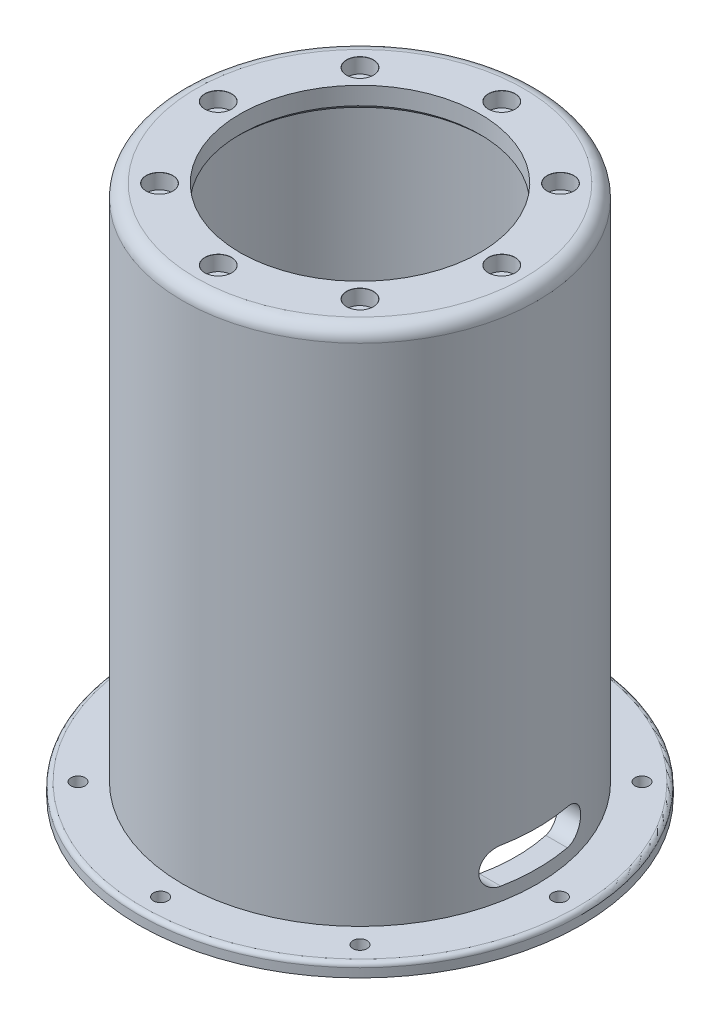
SolidWorks part; units mm, degrees
ref_plane "前视基准面" through (0, 0, 0) normal (0, 0, 1) x (1, 0, 0)
ref_plane "上视基准面" through (0, 0, 0) normal (0, 1, 0) x (1, 0, 0)
ref_plane "右视基准面" through (0, 0, 0) normal (1, 0, 0) x (0, 0, -1)
sketch "草图1" plane through (0, 0, 0) normal (0, 1, 0) x (1, 0, 0)
  circle A0 centre (0, 0) radius 40
  dimension "D1" = 80
extrude "凸台-拉伸1" add sketch "草图1" along normal blind 120
sketch "草图2" plane through (0, 0, 0) normal (0, -1, 0) x (1, 0, 0)
  circle A0 centre (0, 0) radius 35.25
  dimension "D1" = 70.5
extrude "切除-拉伸1" cut sketch "草图2" against normal offset from surface (115 mm away) 5 up to face at (0, 120, 40)
sketch "草图3" plane through (0, 120, 0) normal (0, 1, 0) x (1, 0, 0)
  circle A0 centre (0, 0) radius 27.1
  dimension "D1" = 54.2
extrude "切除-拉伸2" cut sketch "草图3" against normal through all
sketch "草图4" plane through (0, 120, 0) normal (0, 1, 0) x (1, 0, 0)
  circle A0 centre (0, 0) radius 32 construction
  point P3 (0, 32)
  dimension "D1" = 64
hole_wizard "打孔尺寸(%根据)内六角圆柱头螺钉的类型1" positions "草图5" profile "草图6" counterbore size "M3" standard "GB" end condition through all
sketch "草图5" plane through (0, 120, 0) normal (0, 1, 0) x (1, 0, 0)
  point P0 (0, 32)
sketch "草图6" plane through (0, 120, -32) normal (1, 0, 0) x (0, 0, 1)
  line L0 (0, 0) -> (0, 120)
  line L1 (0, 120) -> (1.7, 120)
  line L3 (1.7, 120) -> (1.7, 3.4)
  line L4 (3, 3.4) -> (1.7, 3.4)
  line L5 (3, 3.4) -> (3, 0.025)
  line L6 (3, 0.025) -> (3.025, 0)
  line L7 (3.025, 0) -> (0, 0)
  line L8 (-3, 0.025) -> (-3.025, 0) construction
  line L11 (0, -6.35) -> (0, 107.95) construction
  dimension "通孔孔直径" = 3.4
  dimension "通孔孔深度" = 120
  dimension "柱形沉头孔直径" = 6
  dimension "柱形沉头孔深度" = 3.4
  dimension "近端锥形沉头孔直径" = 6.05
  dimension "近端锥形沉头孔角度" = 90
pattern_circular "阵列(圆周)1" count 8 over 360 about axis through (0, 0, 0) along (0, 1, 0) of "打孔尺寸(%根据)内六角圆柱头螺钉的类型1"
sketch "草图7" plane through (0, 0, 0) normal (0, -1, 0) x (1, 0, 0)
  circle A0 centre (0, 0) radius 50
  circle A1 centre (0, 0) radius 40 construction
  circle A2 centre (0, 0) radius 40
  dimension "D1" = 100
extrude "凸台-拉伸2" add sketch "草图7" against normal blind 3
sketch "草图8" plane through (0, 3, 0) normal (0, 1, 0) x (1, 0, 0)
  circle A2 centre (0, -45) radius 1.6
  circle A3 centre (0, 0) radius 45 construction
  point P7 (0, -45)
  dimension "D1" = 3.2
  dimension "D2" = 90
extrude "切除-拉伸3" cut sketch "草图8" against normal through all
pattern_circular "阵列(圆周)2" count 8 over 360 about axis through (0, 0, 0) along (0, 1, 0) of "切除-拉伸3"
fillet "圆角1" radius 3 1 edges at (0, 120, 40)
chamfer "倒角1" distance 1 angle 45 2 edges at (0, 115, 27.1) (0, 0, -35.25)
fillet "圆角2" radius 1 1 edges at (0, 3, -50)
ref_plane "基准面1" through (40, 0, 0) normal (1, 0, 0) x (0, 0, -1)
sketch "草图9" plane through (40, 0, 0) normal (1, 0, 0) x (0, 0, -1)
  line L0 (-7.5, 10) -> (7.5, 10) construction
  line L1 (-7.5, 14) -> (7.5, 14)
  line L2 (-7.5, 6) -> (7.5, 6)
  line L3 (27.1, 120) -> (-27.1, 120) construction
  arc A0 (-7.5, 14) -> (-7.5, 6) centre (-7.5, 10) ccw
  arc A1 (7.5, 6) -> (7.5, 14) centre (7.5, 10) ccw
  point P2 (0, 10)
  dimension "D2" = 4
  dimension "D1" = 15
  dimension "D3" = 110
extrude "切除-拉伸4" cut sketch "草图9" against normal through all
